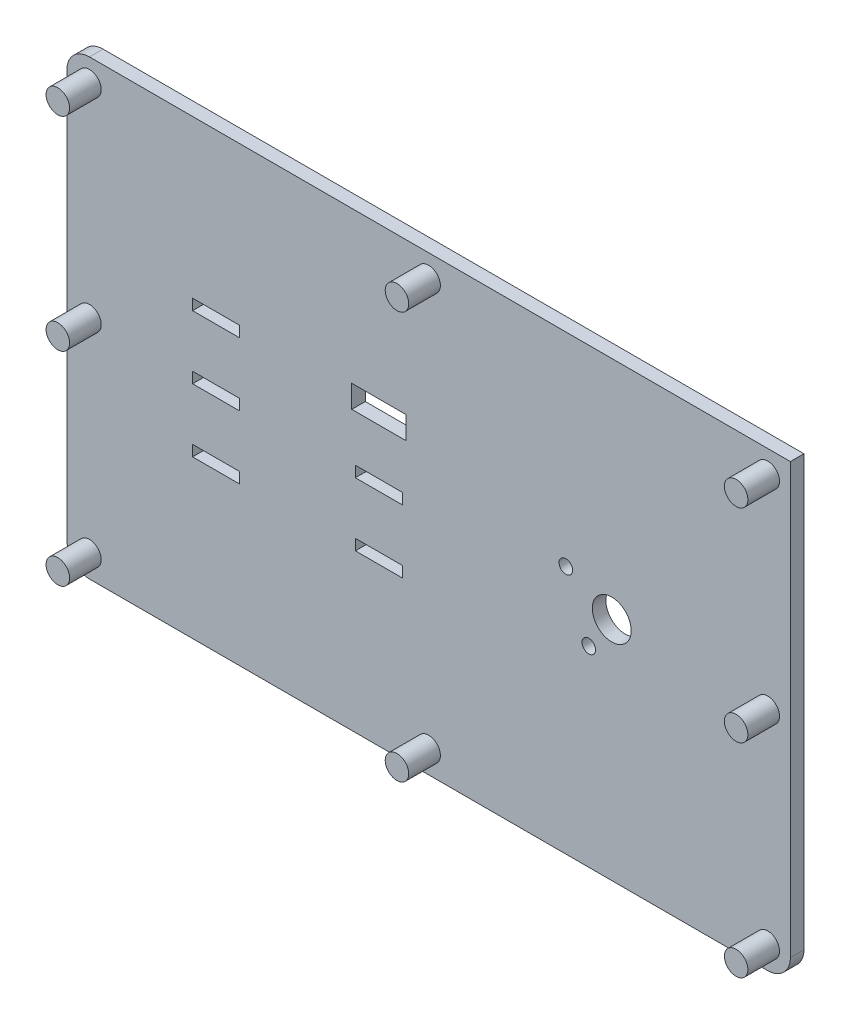
SolidWorks part; units mm, degrees
ref_plane "Front Plane" through (0, 0, 0) normal (1, 0, 0) x (0, 1, 0)
ref_plane "Top Plane" through (0, 0, 0) normal (0, 0, 1) x (0, 1, 0)
ref_plane "Right Plane" through (0, 0, 0) normal (0, 1, 0) x (-1, 0, 0)
sketch "Sketch1" plane through (0, 0, 0) normal (0, 0, 1) x (0, 1, 0)
  line L0 (0, 40) -> (0, -40) construction
  line L1 (25, 0) -> (-25, 0) construction
  line L2 (22.5, 37.5) -> (-22.5, 37.5) construction
  line L3 (-22.5, 37.5) -> (-22.5, -37.5) construction
  line L4 (-25, -40) -> (25, -40) construction
  line L5 (25, -40) -> (25, 40) construction
  line L6 (25, 40) -> (-25, 40) construction
  line L7 (-25, 40) -> (-25, -40) construction
  line L8 (-22.5, -37.5) -> (22.5, -37.5) construction
  line L9 (22.5, -37.5) -> (22.5, 37.5) construction
  line L11 (-25, -40) -> (25, -40)
  line L12 (-25, -40) -> (-25, 40)
  line L17 (-25, 40) -> (25, 40)
  line L18 (25, -40) -> (25, 40)
  line L23 (-25, -40) -> (25, 40) construction
  line L24 (-25, 40) -> (25, -40) construction
  point P24 (0, 0)
extrude "Boss-Extrude5" add sketch "Sketch1" along normal blind 1.5
sketch "Sketch4" plane through (0, 0, 0) normal (0, 0, 1) x (0, 1, 0)
  line L0 (0, 40) -> (0, -40) construction
  line L1 (25, 0) -> (-25, 0) construction
  line L2 (22.5, 37.5) -> (-22.5, 37.5) construction
  line L3 (-22.5, 37.5) -> (-22.5, -37.5) construction
  line L4 (-25, -40) -> (25, -40) construction
  line L5 (25, -40) -> (25, 40) construction
  line L6 (25, 40) -> (-25, 40) construction
  line L7 (-25, 40) -> (-25, -40) construction
  line L8 (-22.5, -37.5) -> (22.5, -37.5) construction
  line L9 (22.5, -37.5) -> (22.5, 37.5) construction
  circle A0 centre (0, 37.5) radius 2.5 construction
  circle A1 centre (-22.5, 37.5) radius 2.5 construction
  circle A2 centre (22.5, 37.5) radius 2.5 construction
  circle A3 centre (-22.5, 0) radius 2.5 construction
  circle A4 centre (22.5, 0) radius 2.5 construction
  circle A5 centre (22.5, -37.5) radius 2.5 construction
  circle A6 centre (-22.5, -37.5) radius 2.5 construction
  circle A7 centre (0, -37.5) radius 2.5 construction
  circle A8 centre (-22.5, 37.5) radius 1.3
  circle A9 centre (0, 37.5) radius 1.3
  circle A10 centre (22.5, 37.5) radius 1.3
  circle A11 centre (-22.5, 0) radius 1.3
  circle A12 centre (22.5, 0) radius 1.3
  circle A13 centre (22.5, -37.5) radius 1.3
  circle A14 centre (0, -37.5) radius 1.3
  circle A15 centre (-22.5, -37.5) radius 1.3
  dimension "D1" = 1.2
extrude "Boss-Extrude6" add sketch "Sketch4" along normal blind 5
sketch "Sketch6" plane through (0, 0, 0) normal (0, 0, 1) x (0, 1, 0)
  line L0 (0, 40) -> (0, -40) construction
  line L1 (25, 40) -> (-25, 40) construction
  line L2 (-25, -40) -> (25, -40) construction
  line L3 (25, 0) -> (-25, 0) construction
  line L4 (25, -40) -> (25, 40) construction
  line L5 (-25, 40) -> (-25, -40) construction
  line L6 (0, 40) -> (0, -1) construction
  line L7 (0, -1) -> (0, -40) construction
  line L8 (-9.6, 17) -> (9.6, 17) construction
  line L9 (-9.6, 17) -> (-9.6, 30) construction
  line L10 (-9.6, 30) -> (9.6, 30) construction
  line L11 (9.6, 17) -> (9.6, 30) construction
  line L12 (-9.6, 17) -> (9.6, 30) construction
  line L13 (-9.6, 30) -> (9.6, 17) construction
  line L14 (-9.6, -1) -> (9.6, -1) construction
  line L15 (-9.6, -1) -> (-9.6, 12) construction
  line L16 (-9.6, 12) -> (9.6, 12) construction
  line L17 (9.6, -1) -> (9.6, 12) construction
  line L18 (-9.6, -1) -> (9.6, 12) construction
  line L19 (-9.6, 12) -> (9.6, -1) construction
  line L20 (-9.75, -29.2467) -> (9.75, -29.2467) construction
  line L21 (-9.75, -29.2467) -> (-9.75, -11.2533) construction
  line L22 (-9.75, -11.2533) -> (9.75, -11.2533) construction
  line L23 (9.75, -29.2467) -> (9.75, -11.2533) construction
  line L24 (-9.75, -29.2467) -> (9.75, -11.2533) construction
  line L25 (-9.75, -11.2533) -> (9.75, -29.2467) construction
  line L26 (-9.6, 23.5) -> (9.6, 23.5) construction
  line L27 (6.4, 20.9) -> (7.6, 20.9)
  line L28 (-0.6, 20.9) -> (0.6, 20.9)
  line L29 (-0.6, 20.9) -> (-0.6, 26.1)
  line L30 (-0.6, 26.1) -> (0.6, 26.1)
  line L31 (0.6, 20.9) -> (0.6, 26.1)
  line L32 (-0.6, 20.9) -> (0.6, 26.1) construction
  line L33 (-0.6, 26.1) -> (0.6, 20.9) construction
  line L34 (7.6, 20.9) -> (7.6, 26.1)
  line L35 (6.4, 26.1) -> (7.6, 26.1)
  line L36 (6.4, 20.9) -> (6.4, 26.1)
  line L37 (-0.6, 20.9) -> (0.6, 20.9)
  line L38 (0.6, 20.9) -> (0.6, 26.1)
  line L39 (-0.6, 26.1) -> (0.6, 26.1)
  line L40 (-0.6, 20.9) -> (-0.6, 26.1)
  line L41 (-7.6, 20.9) -> (-6.4, 20.9)
  line L42 (-6.4, 20.9) -> (-6.4, 26.1)
  line L43 (-7.6, 26.1) -> (-6.4, 26.1)
  line L44 (-7.6, 20.9) -> (-7.6, 26.1)
  line L45 (-9.6, 5.5) -> (9.6, 5.5) construction
  line L46 (-9.75, -20.25) -> (9.75, -20.25) construction
  line L47 (-0.6, 2.9) -> (0.6, 2.9)
  line L48 (-0.6, 2.9) -> (-0.6, 8.1)
  line L49 (-0.6, 8.1) -> (0.6, 8.1)
  line L50 (0.6, 2.9) -> (0.6, 8.1)
  line L51 (-0.6, 2.9) -> (0.6, 8.1) construction
  line L52 (-0.6, 8.1) -> (0.6, 2.9) construction
  line L53 (-7.6, 2.9) -> (-6.4, 2.9)
  line L54 (-7.6, 2.9) -> (-7.6, 8.1)
  line L55 (-7.6, 8.1) -> (-6.4, 8.1)
  line L56 (-6.4, 2.9) -> (-6.4, 8.1)
  line L57 (-7.6, 2.9) -> (-6.4, 8.1) construction
  line L58 (-7.6, 8.1) -> (-6.4, 2.9) construction
  line L59 (5.75, 2.5) -> (8.25, 2.5)
  line L60 (5.75, 2.5) -> (5.75, 8.5)
  line L61 (5.75, 8.5) -> (8.25, 8.5)
  line L62 (8.25, 2.5) -> (8.25, 8.5)
  line L63 (5.75, 2.5) -> (8.25, 8.5) construction
  line L64 (5.75, 8.5) -> (8.25, 2.5) construction
  line L65 (7, 9.6862) -> (7, 0) construction
  line L66 (-7, 12) -> (-7, 0) construction
  circle A0 centre (0, -20.25) radius 2.15
  circle A1 centre (-3.81, -17.71) radius 0.75
  circle A3 centre (2.54, -15.17) radius 0.75
  point P13 (0, 23.5)
  point P18 (0, 5.5)
  point P24 (0, -20.25)
  point P30 (0, 23.5)
  point P49 (0, 5.5)
  point P54 (-7, 5.5)
  point P59 (7, 5.5)
  dimension "D11" = 1.5
  dimension "D12" = 2.54
  dimension "D13" = 3.81
  dimension "D14" = 1.5
  dimension "D15" = 2
  dimension "D16" = 5.08
  dimension "D17" = 2.54
  dimension "D22" = 4.3
  dimension "D1" = 19.2
  dimension "D2" = 13
  dimension "D3" = 19.2
  dimension "D4" = 13
  dimension "D5" = 19.5
  dimension "D6" = 5.2
  dimension "D7" = 1.2
  dimension "D9" = 5.2
  dimension "D10" = 1.2
  dimension "D18" = 7
  dimension "D19" = 7
  dimension "D20" = 2.5
  dimension "D21" = 6
  dimension "D8" = 2
extrude "Cut-Extrude1" cut sketch "Sketch6" along normal blind 10 contours A0 | A3 | A1 | L50 L49 L48 L47 | L62 L61 L60 L59 | L56 L55 L54 L53 | L42 L43 L44 L41 | L31 L30 L29 L28 | L34 L35 L36 L27
fillet "Fillet1" radius 2.5 3 edges at (-40, -25, 0.75) (-40, 25, 0.75) (40, -25, 0.75)
